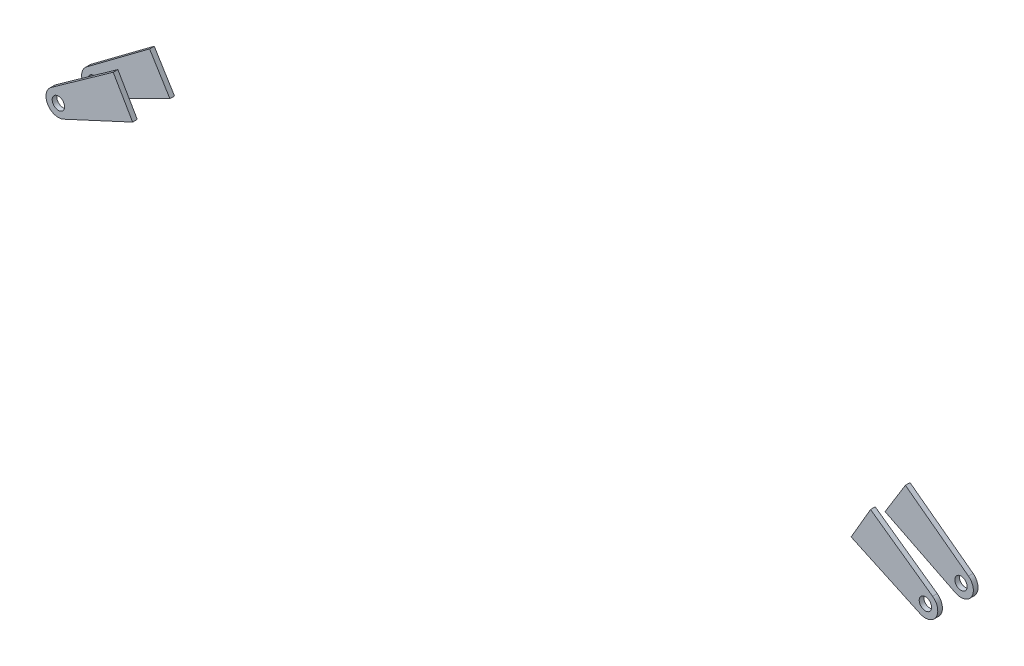
SolidWorks part; units mm, degrees
material "AISI 4130 Steel, normalized at 870C"
ref_plane "Front Plane" through (0, 0, 0) normal (0, 0, 1) x (1, 0, 0)
ref_plane "Top Plane" through (0, 0, 0) normal (0, 1, 0) x (1, 0, 0)
ref_plane "Right Plane" through (0, 0, 0) normal (1, 0, 0) x (0, 0, -1)
sketch3d "3DSketch1"
  line L0 (280, -1980, 297) -> (280, -1980, 307) construction
  line L1 (240, -1960, 350) -> (230, -1935, 95) construction
  line L2 (240, -1960, 350) -> (230, -1935, 95) construction
  line L3 (276.6368, -1987.2587, 307) -> (232.0349, -1966.593, 307)
  line L4 (232.0349, -1966.593, 307) -> (244.5925, -1944.9757, 307)
  line L5 (244.5925, -1944.9757, 307) -> (284.6393, -1973.4826, 307)
  circle A0 centre (280, -1980, 307) radius 4
  arc A1 (276.6368, -1987.2587, 307) -> (284.6393, -1973.4826, 307) centre (280, -1980, 307) ccw
  point P8 (280, -1980, 311)
  point P11 (280, -1980, 315)
  point P15 (354.997, -2023.566, 307)
  point P16 (354.997, -2023.566, 307)
  point P17 (238.3137, -1955.7843, 307)
  dimension "D1" = 8
  dimension "D2" = 4
  dimension "D3" = 25
extrude "Boss-Extrude-U" add sketch "3DSketch1" along a picked direction on the side of the normal blind 3 contours L5 A1 L3 L4 | A0
sketch3d "3DSketch2"
  line L3 (280, -1980, 297) -> (280, -1980, 287) construction
  line L4 (240, -1960, 350) -> (230, -1935, 95) construction
  line L5 (240, -1960, 350) -> (230, -1935, 95) construction
  line L6 (276.4267, -1987.1576, 287) -> (230.9708, -1964.4647, 287)
  line L7 (284.7883, -1973.5912, 287) -> (244.088, -1943.1824, 287)
  line L8 (230.9708, -1964.4647, 287) -> (244.088, -1943.1824, 287)
  circle A2 centre (280, -1980, 287) radius 4
  arc A3 (276.4267, -1987.1576, 287) -> (284.7883, -1973.5912, 287) centre (280, -1980, 287) ccw
  point P8 (280, -1980, 291)
  point P12 (280, -1980, 295)
  point P15 (237.5294, -1953.8235, 287)
  dimension "D1" = 8
  dimension "D2" = 4
  dimension "D3" = 25
extrude "Boss-Extrude-L" add sketch "3DSketch2" along a picked direction on the side against the normal blind 3 contours L7 L8 L6 A3 | A2
mirror "Mirror1" about plane through (0, 0, 0) normal (1, 0, 0) of bodies 106 109
